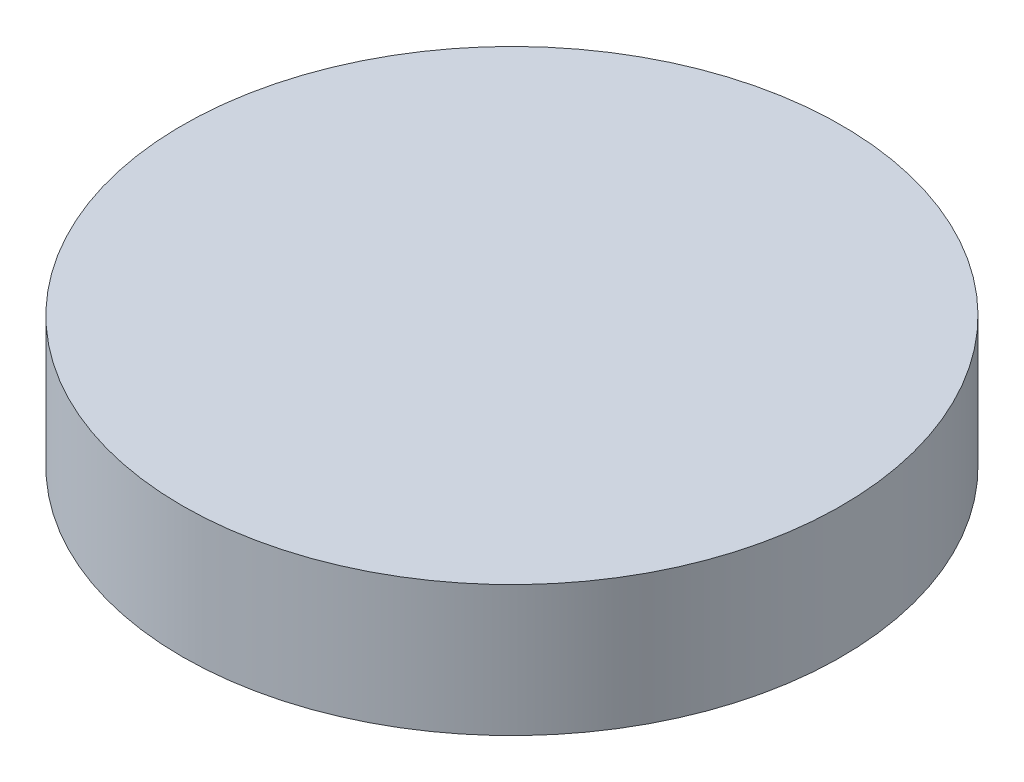
SolidWorks part; units mm, degrees
ref_plane "Front Plane" through (0, 0, 0) normal (0, 0, 1) x (1, 0, 0)
ref_plane "Top Plane" through (0, 0, 0) normal (0, 1, 0) x (1, 0, 0)
ref_plane "Right Plane" through (0, 0, 0) normal (1, 0, 0) x (0, 0, -1)
sketch "Sketch1" plane through (0, 0, 0) normal (0, 1, 0) x (1, 0, 0)
  circle A0 centre (0, 0) radius 63
extrude "Boss-Extrude1" add sketch "Sketch1" along normal blind 25
sketch "Sketch2" plane through (0, 0, 0) normal (0, -1, 0) x (1, 0, 0)
  circle A0 centre (0, 0) radius 60
extrude "Cut-Extrude2" cut sketch "Sketch2" against normal blind 20 contours A0
sketch "Sketch3" plane through (0, 20, 0) normal (0, -1, 0) x (1, 0, 0)
  circle A0 centre (0, 0) radius 7.5
extrude "Boss-Extrude2" add sketch "Sketch3" along normal blind 20
sketch "Sketch4" plane through (0, 20, 0) normal (0, -1, 0) x (1, 0, 0)
  line L0 (57.1384, 23.2733) -> (23.9462, 56.8596) construction
  line L1 (-23.2733, 57.1384) -> (-56.8596, 23.9462) construction
  line L2 (-56.8596, 23.9462) -> (-57.1384, -23.2733) construction
  line L3 (-57.1384, -23.2733) -> (-23.9462, -56.8596) construction
  line L4 (-23.9462, -56.8596) -> (23.2733, -57.1384) construction
  line L5 (23.2733, -57.1384) -> (56.8596, -23.9462) construction
  line L6 (56.8596, -23.9462) -> (57.1384, 23.2733) construction
  line L7 (23.9462, 56.8596) -> (-23.2733, 57.1384) construction
  line L8 (-23.2733, 57.1384) -> (23.2733, -57.1384)
  line L9 (23.9462, 56.8596) -> (-23.9462, -56.8596)
  line L10 (57.1384, 23.2733) -> (-57.1384, -23.2733)
  line L11 (56.8596, -23.9462) -> (-56.8596, 23.9462)
  circle A0 centre (0, 0) radius 57 construction
extrude "Extrude-Thin3" add sketch "Sketch4" along normal through all thin
